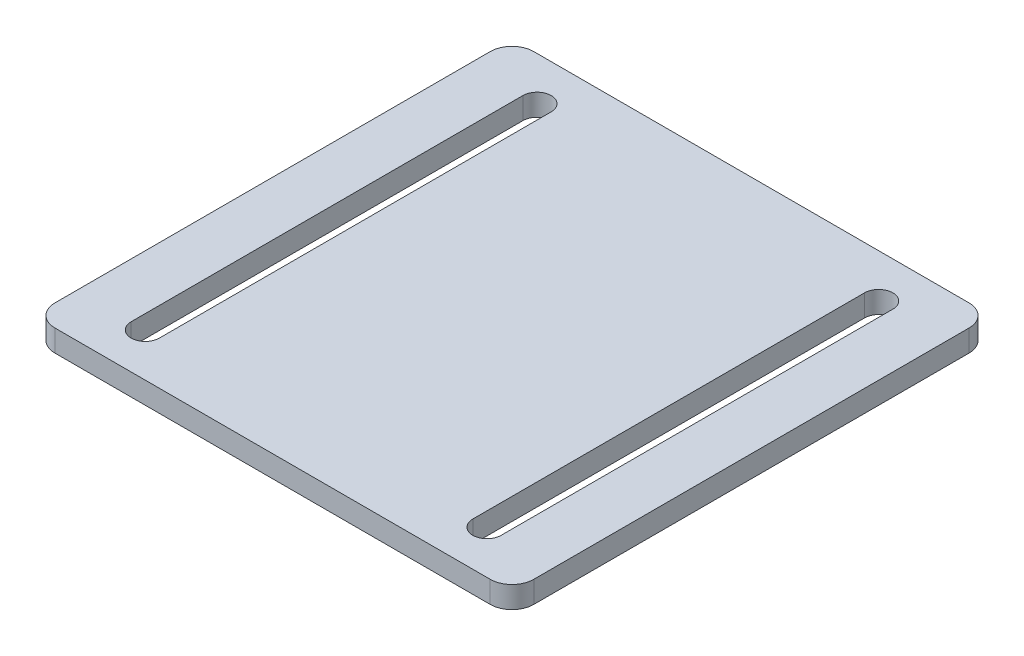
SolidWorks part; units mm, degrees
ref_plane "Front Plane" through (0, 0, 0) normal (0, 0, 1) x (1, 0, 0)
ref_plane "Top Plane" through (0, 0, 0) normal (0, 1, 0) x (1, 0, 0)
ref_plane "Right Plane" through (0, 0, 0) normal (1, 0, 0) x (0, 0, -1)
sketch "Sketch1" plane through (0, 0, 0) normal (0, 1, 0) x (1, 0, 0)
  line L0 (0, 0) -> (-51.7758, 0) construction
  line L1 (0, 0) -> (48.6188, 0) construction
  line L2 (0, 0) -> (0, 40.4104) construction
  line L3 (0, 0) -> (0, -34.0963) construction
  line L4 (-27.94, 0) -> (-27.94, 25.4)
  line L5 (-25.4, 27.94) -> (0, 27.94)
  line L6 (0, 27.94) -> (25.4, 27.94)
  line L7 (27.94, 25.4) -> (27.94, 0)
  line L8 (27.94, 0) -> (27.94, -25.4)
  line L9 (25.4, -27.94) -> (0, -27.94)
  line L10 (0, -27.94) -> (-25.4, -27.94)
  line L11 (-27.94, -25.4) -> (-27.94, 0)
  line L13 (-19.939, 22.86) -> (-19.939, -22.86) construction
  line L14 (-18.288, 22.86) -> (-18.288, -22.86)
  line L15 (-21.59, 22.86) -> (-21.59, -22.86)
  line L16 (19.939, 22.86) -> (19.939, -22.86) construction
  line L17 (18.288, 22.86) -> (18.288, -22.86)
  line L18 (21.59, 22.86) -> (21.59, -22.86)
  arc A0 (-18.288, 22.86) -> (-21.59, 22.86) centre (-19.939, 22.86) ccw
  arc A1 (-21.59, -22.86) -> (-18.288, -22.86) centre (-19.939, -22.86) ccw
  arc A2 (18.288, 22.86) -> (21.59, 22.86) centre (19.939, 22.86) cw
  arc A3 (21.59, -22.86) -> (18.288, -22.86) centre (19.939, -22.86) cw
  arc A4 (-25.4, -27.94) -> (-27.94, -25.4) centre (-25.4, -25.4) cw
  arc A5 (27.94, -25.4) -> (25.4, -27.94) centre (25.4, -25.4) cw
  arc A6 (25.4, 27.94) -> (27.94, 25.4) centre (25.4, 25.4) cw
  arc A7 (-27.94, 25.4) -> (-25.4, 27.94) centre (-25.4, 25.4) cw
  point P17 (-19.939, 0)
  point P24 (19.939, 0)
  point P31 (-27.94, -27.94)
  point P36 (27.94, 27.94)
  point P39 (-27.94, 27.94)
  dimension "D8" = 2.54
  dimension "D1" = 27.94
  dimension "D2" = 27.94
  dimension "D3" = 27.94
  dimension "D4" = 27.94
  dimension "D5" = 45.72
  dimension "D6" = 6.35
  dimension "D7" = 3.302
extrude "Boss-Extrude1" add sketch "Sketch1" along normal blind 2.54
